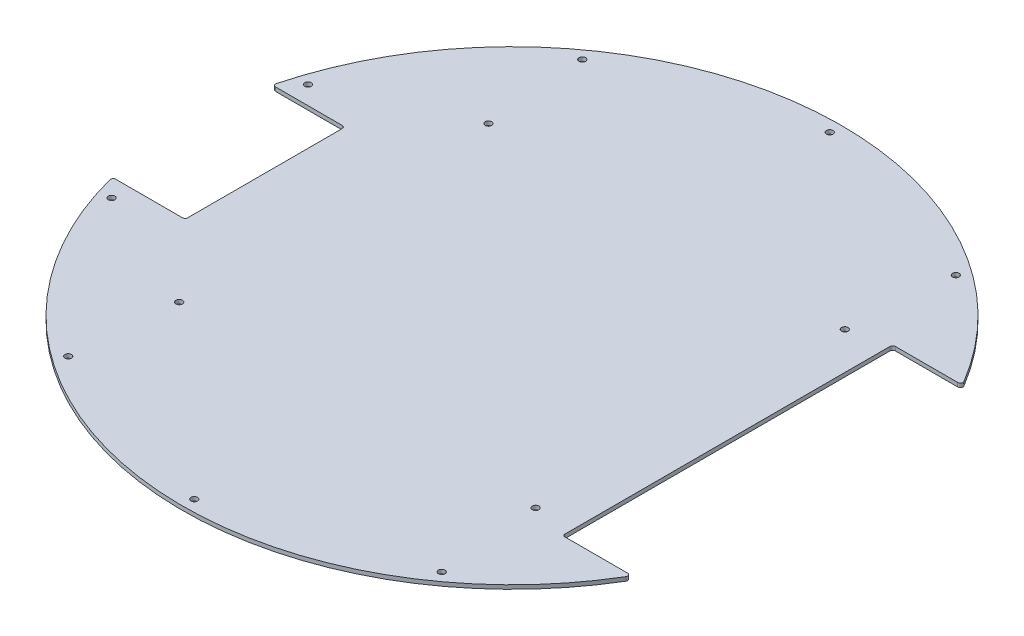
SolidWorks part; units mm, degrees
ref_plane "Front Plane" through (0, 0, 0) normal (0, 0, 1) x (1, 0, 0)
ref_plane "Top Plane" through (0, 0, 0) normal (0, 1, 0) x (1, 0, 0)
ref_plane "Right Plane" through (0, 0, 0) normal (1, 0, 0) x (0, 0, -1)
sketch "Sketch1" plane through (0, 0, 0) normal (0, 1, 0) x (1, 0, 0)
  circle A0 centre (0, 0) radius 251.5
extrude "Boss-Extrude1" add sketch "Sketch1" along normal blind 3
sketch "Sketch2" plane through (0, 3, 0) normal (0, 1, 0) x (1, 0, 0)
  line L0 (0, -1.65) -> (0, 1.65) construction
  line L1 (-1.65, 0) -> (1.65, 0) construction
  circle A0 centre (-136, 118) radius 2.5
  circle A1 centre (136, 118) radius 2.5
  circle A2 centre (136, -118) radius 2.5
  circle A3 centre (-136, -118) radius 2.5
  dimension "D1" = 136
  dimension "D2" = 118
extrude "Cut-Extrude1" cut sketch "Sketch2" against normal blind 5
sketch "Sketch4" plane through (0, 3, 0) normal (0, 1, 0) x (1, 0, 0)
  circle A0 centre (0, 242.5) radius 2.5
  circle A1 centre (142.5379, 196.1866) radius 2.5
  circle A2 centre (230.6312, 74.9366) radius 2.5
  circle A3 centre (230.6312, -74.9366) radius 2.5
  circle A4 centre (142.5379, -196.1866) radius 2.5
  circle A5 centre (0, -242.5) radius 2.5
  circle A6 centre (-142.5379, -196.1866) radius 2.5
  circle A7 centre (-230.6312, -74.9366) radius 2.5
  circle A8 centre (-230.6312, 74.9366) radius 2.5
  circle A9 centre (-142.5379, 196.1866) radius 2.5
  point P23 (0, 0)
  dimension "D1" = 242.5
  dimension "D2" = 10
extrude "Cut-Extrude3" cut sketch "Sketch4" against normal blind 5
sketch "Sketch5" plane through (0, 3, 0) normal (0, 1, 0) x (1, 0, 0)
  line L0 (-228, 60) -> (-192.5, 60) construction
  line L1 (-188.5, 61) -> (-262.4687, 61)
  line L2 (-188.5, 61) -> (-188.5, -61)
  line L3 (-188.5, -61) -> (-262.4687, -61)
  line L4 (-262.4687, 61) -> (-262.4687, -61)
  line L5 (-189.5, 0) -> (-189.5, 60) construction
  line L6 (-192.5, -60) -> (-228, -60) construction
  line L7 (221.6873, 125) -> (168.5835, 125) construction
  line L8 (164.5, 126) -> (286.7372, 126)
  line L9 (164.5, 126) -> (164.5, -126)
  line L10 (164.5, -126) -> (286.7372, -126)
  line L11 (286.7372, 126) -> (286.7372, -126)
  line L12 (165.5, 125) -> (165.5, -125) construction
  line L13 (221.6873, -125) -> (168.5835, -125) construction
  dimension "D1" = 1
  dimension "D2" = 1
  dimension "D3" = 1
  dimension "D4" = 1
  dimension "D5" = 1
  dimension "D6" = 1
extrude "Cut-Extrude4" cut sketch "Sketch5" against normal blind 10
fillet "Fillet1" radius 2 8 edges at (-243.9903, 1.5, 61) (-243.9903, 1.5, -61) (217.6609, 1.5, 126) (164.5, 1.5, 126) (217.6609, 1.5, -126) (164.5, 1.5, -126) (-188.5, 1.5, 61) (-188.5, 1.5, -61)
